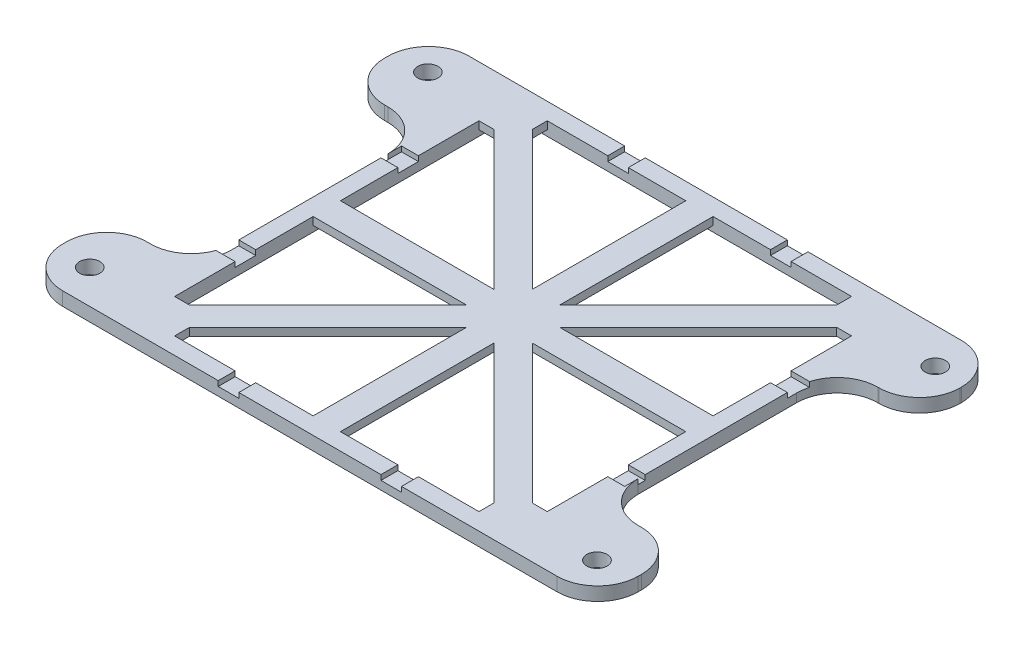
SolidWorks part; units mm, degrees
ref_plane "Front Plane" through (0, 0, 0) normal (0, 0, 1) x (1, 0, 0)
ref_plane "Top Plane" through (0, 0, 0) normal (0, 1, 0) x (1, 0, 0)
ref_plane "Right Plane" through (0, 0, 0) normal (1, 0, 0) x (0, 0, -1)
sketch "Sketch1" plane through (0, 0, 0) normal (0, 1, 0) x (1, 0, 0)
  line L1 (-55.1, 55.1) -> (55.1, 55.1)
  line L2 (-55.1, 55.1) -> (-55.1, -55.1)
  line L3 (-55.1, -55.1) -> (55.1, -55.1)
  line L4 (55.1, 55.1) -> (55.1, -55.1)
  line L5 (-55.1, 55.1) -> (55.1, -55.1) construction
  line L6 (-55.1, -55.1) -> (55.1, 55.1) construction
  line L7 (-60.1, 60.1) -> (60.1, 60.1)
  line L8 (-60.1, 60.1) -> (-60.1, -60.1)
  line L9 (-60.1, -60.1) -> (60.1, -60.1)
  line L10 (60.1, 60.1) -> (60.1, -60.1)
  line L11 (-60.1, 60.1) -> (60.1, -60.1) construction
  line L12 (-60.1, -60.1) -> (60.1, 60.1) construction
  point P0 (0, 0)
  point P6 (0, 0)
  dimension "D1" = 5
  dimension "D2" = 110.2
extrude "Boss-Extrude1" add sketch "Sketch1" along normal blind 4
sketch "Sketch2" plane through (0, 4, 0) normal (0, 1, 0) x (1, 0, 0)
  line L1 (-55.1, 55.1) -> (-45, 55.1)
  line L2 (-55.1, 55.1) -> (-55.1, 45)
  line L3 (-55.1, 45) -> (-45, 45)
  line L4 (-45, 55.1) -> (-45, 45)
  line L5 (55.1, 55.1) -> (45, 55.1)
  line L6 (55.1, 55.1) -> (55.1, 45)
  line L7 (55.1, 45) -> (45, 45)
  line L8 (45, 55.1) -> (45, 45)
  line L9 (55.1, -55.1) -> (45, -55.1)
  line L10 (55.1, -55.1) -> (55.1, -45)
  line L11 (55.1, -45) -> (45, -45)
  line L12 (45, -55.1) -> (45, -45)
  line L13 (-55.1, -55.1) -> (-45, -55.1)
  line L14 (-55.1, -55.1) -> (-55.1, -45)
  line L15 (-55.1, -45) -> (-45, -45)
  line L16 (-45, -55.1) -> (-45, -45)
extrude "Boss-Extrude2" add sketch "Sketch2" against normal blind 2.3
sketch "Sketch3" plane through (0, 0, 0) normal (0, -1, 0) x (-1, 0, 0)
  line L0 (75.1, -50.1) -> (75.1, 49.9)
  line L1 (60.1, -60.1) -> (85.1, -60.1)
  line L2 (60.1, -60.1) -> (60.1, -35.1)
  line L3 (60.1, -35.1) -> (85.1, -35.1)
  line L4 (85.1, -60.1) -> (85.1, -35.1)
  line L5 (-60.1, -60.1) -> (-85.1, -60.1)
  line L6 (-60.1, -60.1) -> (-60.1, -35.1)
  line L7 (-60.1, -35.1) -> (-85.1, -35.1)
  line L8 (-85.1, -60.1) -> (-85.1, -35.1)
  line L9 (60.1, 60.1) -> (85.1, 60.1)
  line L10 (60.1, 60.1) -> (60.1, 35.1)
  line L11 (60.1, 35.1) -> (85.1, 35.1)
  line L12 (85.1, 60.1) -> (85.1, 35.1)
  line L13 (75.1, -50.1) -> (-74.9, -50.1)
  line L14 (60.1, -60.1) -> (-60.1, -60.1) construction
  line L15 (-60.1, 60.1) -> (-84.45, 60.1)
  line L16 (-60.1, 60.1) -> (-60.1, 35.75)
  line L17 (-60.1, 35.75) -> (-84.45, 35.75)
  line L18 (-84.45, 60.1) -> (-84.45, 35.75)
  circle A0 centre (75.1, -50.1) radius 3
  circle A1 centre (-74.9, -50.1) radius 3
  circle A2 centre (75.1, 49.9) radius 3
  circle A3 centre (-75.2602, 49.5981) radius 3
  dimension "D1" = 150
  dimension "D2" = 100
  dimension "D4" = 6
  dimension "D5" = 0
  dimension "D6" = 15
  dimension "D7" = 10
  dimension "D3" = 25
extrude "Boss-Extrude3" add sketch "Sketch3" against normal blind 4
fillet "Fillet1" radius 12 12 edges at (85.1, 2, 60.1) (85.1, 2, 35.1) (60.1, 2, 35.1) (-85.1, 2, -60.1) (-85.1, 2, -35.1) (-60.1, 2, -35.1) (-60.1, 2, 35.1) (-85.1, 2, 60.1) (-85.1, 2, 35.1) (84.45, 2, -60.1) (84.45, 2, -35.75) (60.1, 2, -35.75)
sketch "Sketch5" plane through (0, 0, 0) normal (0, -1, 0) x (1, 0, 0)
  circle A0 centre (0, 0) radius 5.4173
extrude "Boss-Extrude4" add sketch "Sketch5" along normal blind 10 separate body
sketch "Sketch4" plane through (0, 0, 0) normal (0, -1, 0) x (-1, 0, 0)
  line L1 (64.7823, -27.1) -> (55.1, -27.1)
  line L2 (64.7823, -27.1) -> (64.7823, -21.0233)
  line L3 (64.7823, -21.0233) -> (55.1, -21.0233)
  line L4 (55.1, -27.1) -> (55.1, -21.0233)
  line L5 (55.1, 55.1) -> (55.1, -55.1) construction
  line L6 (55.1, -55.1) -> (-55.1, -55.1) construction
  line L7 (55.1, -55.1) -> (-0.4864, 0.4864)
  line L8 (21.0233, -64.7823) -> (21.0233, -55.1)
  line L9 (27.1, -55.1) -> (21.0233, -55.1)
  line L10 (27.1, -64.7823) -> (27.1, -55.1)
  line L11 (27.1, -64.7823) -> (21.0233, -64.7823)
  line M17 (-73.1, -60.1) -> (73.1, -60.1)
  arc M22 (72.1, -35.1) -> (60.1, -23.1) centre (72.1, -23.1) cw
  line M23 (60.1, -23.1) -> (60.1, 23.1)
  line M31 (55.1, 55.1) -> (55.1, -55.1)
  line M32 (55.1, -55.1) -> (-55.1, -55.1)
  dimension "D1" = 28
extrude "Cut-Extrude1" cut sketch "Sketch4" against normal blind 10 from offset 2.5 contours L2 L3 L1 M23 M22 | L3 L1 M23 M31 M22 | L10 L8 M17 M32 offset against normal yes
pattern_circular "CirPattern1" count 4 over 360 about axis through (0, 0, 0) along (0, 1, 0) of "Cut-Extrude1"
sketch "Sketch6" plane through (0, -10, 0) normal (0, -1, 0) x (1, 0, 0)
  circle A0 centre (0, 0) radius 22.0946
extrude "Cut-Extrude2" cut sketch "Sketch6" against normal blind 10
sketch "Sketch8" plane through (0, 1.7, 0) normal (0, -1, 0) x (-1, 0, 0)
  line L0 (55.9197, 50.2148) -> (-50.2148, -55.9197)
  line L1 (4.034, 75.0485) -> (-4.034, 75.0485)
  line L2 (4.034, 75.0485) -> (4.034, -75.0485)
  line L3 (4.034, -75.0485) -> (-4.034, -75.0485)
  line L4 (-4.034, 75.0485) -> (-4.034, -75.0485)
  line L5 (4.034, 75.0485) -> (-4.034, -75.0485) construction
  line L6 (4.034, -75.0485) -> (-4.034, 75.0485) construction
  line L11 (55.9197, 50.2148) -> (50.2148, 55.9197)
  line L12 (50.2148, 55.9197) -> (-55.9197, -50.2148)
  line L13 (-50.2148, -55.9197) -> (-55.9197, -50.2148)
  line L14 (75.0485, -4.034) -> (-75.0485, -4.034)
  line L15 (75.0485, -4.034) -> (75.0485, 4.034)
  line L16 (75.0485, 4.034) -> (-75.0485, 4.034)
  line L17 (-75.0485, -4.034) -> (-75.0485, 4.034)
  line L18 (50.2148, -55.9197) -> (-55.9197, 50.2148)
  line L19 (50.2148, -55.9197) -> (55.9197, -50.2148)
  line L20 (55.9197, -50.2148) -> (-50.2148, 55.9197)
  line L21 (-55.9197, 50.2148) -> (-50.2148, 55.9197)
  line L22 (-4.034, -75.0485) -> (-4.034, 75.0485)
  line L23 (-4.034, -75.0485) -> (4.034, -75.0485)
  line L24 (4.034, -75.0485) -> (4.034, 75.0485)
  line L25 (-4.034, 75.0485) -> (4.034, 75.0485)
  line L26 (-55.9197, -50.2148) -> (50.2148, 55.9197)
  line L27 (-55.9197, -50.2148) -> (-50.2148, -55.9197)
  line L28 (-50.2148, -55.9197) -> (55.9197, 50.2148)
  line L29 (50.2148, 55.9197) -> (55.9197, 50.2148)
  line L30 (-75.0485, 4.034) -> (75.0485, 4.034)
  line L31 (-75.0485, 4.034) -> (-75.0485, -4.034)
  line L32 (-75.0485, -4.034) -> (75.0485, -4.034)
  line L33 (75.0485, 4.034) -> (75.0485, -4.034)
  line L34 (-50.2148, 55.9197) -> (55.9197, -50.2148)
  line L35 (-50.2148, 55.9197) -> (-55.9197, 50.2148)
  line L36 (-55.9197, 50.2148) -> (50.2148, -55.9197)
  line L37 (55.9197, -50.2148) -> (50.2148, -55.9197)
  point P0 (0, 0)
  point P6 (0, 0)
  point P38 (0, 0)
  line M10 (55.1, -45) -> (45, -45)
  line M11 (45, -45) -> (45, -55.1)
  dimension "D1" = 8
extrude "Boss-Extrude5" add sketch "Sketch8" against normal up to surface (2.3 mm away) contours L20 L14 L2 L18 M10 M11 | L2 L18 L0 L4 L3 | L4 L14 L12 L13 L0 | L12 L18 L16 L17 L14 | L21 L18 L16 L4 L20 | L20 L12 L2 L1 L4 | L16 L0 L11 L12 L2 | L20 L14 L15 L16 L0 | L0 L18 L14 L4 | L18 L2 L14 L0 | L14 L20 L0 L2 | L20 L0 L16 L2 | L20 L16 L2 L12 | L12 L20 L4 L16 | L18 L12 L4 L16 | L4 L18 L12 L14 | L18 L0 L14 | L14 L2 L0 | L0 L20 L2 | L20 L2 L16 | L12 L16 L4 | L18 L4 L12 | L14 L18 L4 | L2 L20 L16 L12 L4 L18 L14 L0 | L16 L20 L12 up to face at (0, 4, 57.6)
sketch "Sketch9" plane through (0, 1.7, 0) normal (0, -1, 0) x (-1, 0, 0)
  line L0 (73.1, -60.1) -> (-73.1, -60.1) construction
  line L1 (10.2996, -84.364) -> (-7.4429, -84.364)
  line L2 (10.2996, -84.364) -> (10.2996, -60.1)
  line L3 (10.2996, -60.1) -> (-7.4429, -60.1)
  line L4 (-7.4429, -84.364) -> (-7.4429, -60.1)
  line L5 (-84.364, -10.2996) -> (-60.1, -10.2996)
  line L6 (-84.364, -10.2996) -> (-84.364, 7.4429)
  line L7 (-84.364, 7.4429) -> (-60.1, 7.4429)
  line L8 (-60.1, -10.2996) -> (-60.1, 7.4429)
  line L9 (-10.2996, 84.364) -> (-10.2996, 60.1)
  line L10 (-10.2996, 84.364) -> (7.4429, 84.364)
  line L11 (7.4429, 84.364) -> (7.4429, 60.1)
  line L12 (-10.2996, 60.1) -> (7.4429, 60.1)
  line L13 (84.364, 10.2996) -> (60.1, 10.2996)
  line L14 (84.364, 10.2996) -> (84.364, -7.4429)
  line L15 (84.364, -7.4429) -> (60.1, -7.4429)
  line L16 (60.1, 10.2996) -> (60.1, -7.4429)
  point P21 (0, 0)
  dimension "D1" = 4
extrude "Cut-Extrude3" cut sketch "Sketch9" against normal blind 10
